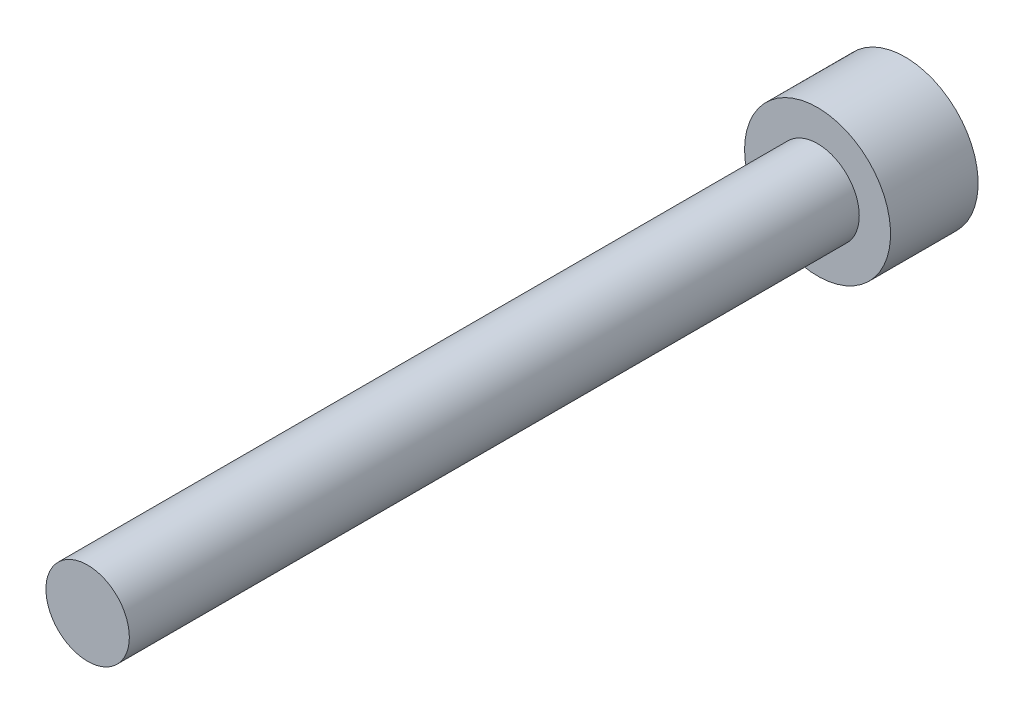
SolidWorks part; units mm, degrees
ref_plane "Front Plane" through (0, 0, 0) normal (0, 0, 1) x (1, 0, 0)
ref_plane "Top Plane" through (0, 0, 0) normal (0, 1, 0) x (1, 0, 0)
ref_plane "Right Plane" through (0, 0, 0) normal (1, 0, 0) x (0, 0, -1)
sketch "Sketch1" plane through (0, 0, 0) normal (0, 0, 1) x (1, 0, 0)
  circle A0 centre (0, 0) radius 2
  dimension "D1" = 4
extrude "Boss-Extrude1" add sketch "Sketch1" along normal blind 35
sketch "Sketch2" plane through (0, 0, 0) normal (0, 0, -1) x (-1, 0, 0)
  circle A0 centre (0, 0) radius 3.5
  dimension "D1" = 7
extrude "Boss-Extrude2" add sketch "Sketch2" along normal blind 4.2
